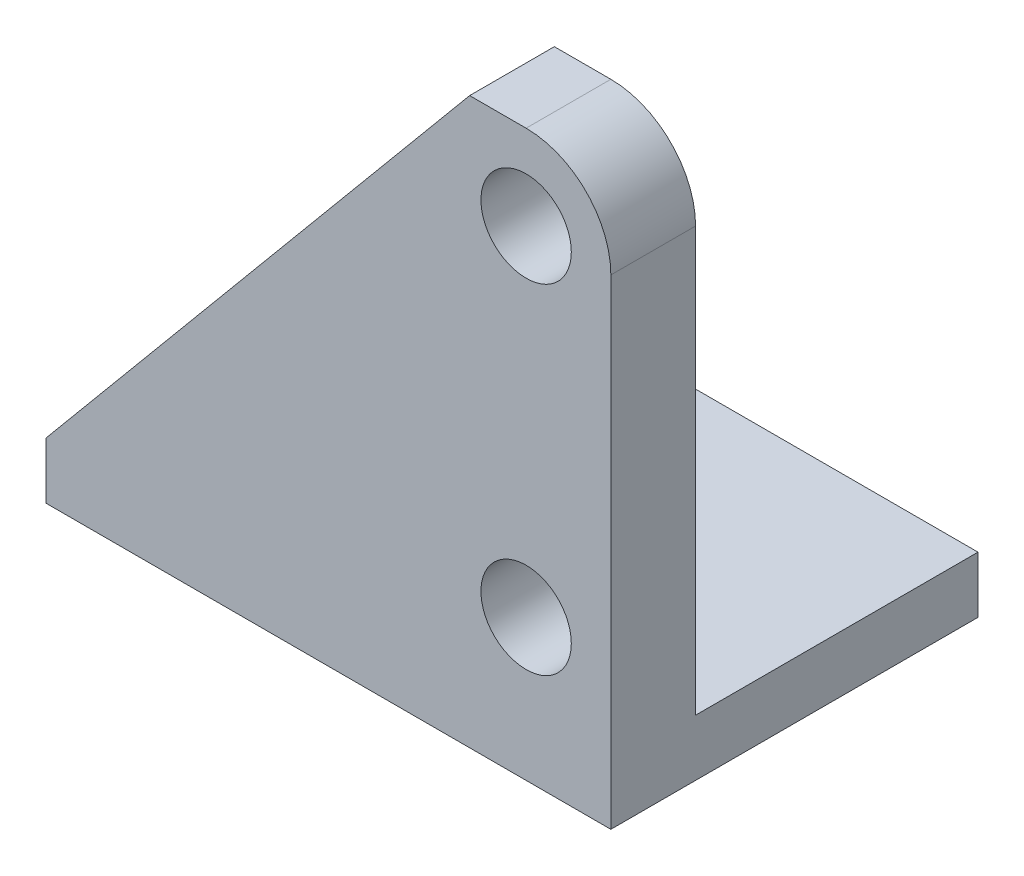
SolidWorks part; units mm, degrees
ref_plane "前视基准面" through (0, 0, 0) normal (0, 0, 1) x (1, 0, 0)
ref_plane "上视基准面" through (0, 0, 0) normal (0, 1, 0) x (1, 0, 0)
ref_plane "右视基准面" through (0, 0, 0) normal (1, 0, 0) x (0, 0, -1)
sketch "草图1" plane through (0, 0, 0) normal (0, 0, 1) x (1, 0, 0)
  line L1 (0, 0) -> (20, 0)
  line L2 (0, 0) -> (0, 20)
  line L3 (0, 20) -> (17, 20)
  line L4 (20, 0) -> (20, 17)
  circle A0 centre (17, 17) radius 1.6
  circle A2 centre (17, 5) radius 1.6
  arc A3 (20, 17) -> (17, 20) centre (17, 17) ccw
  dimension "D1" = 2
  dimension "D2" = 3
extrude "凸台-拉伸1" add sketch "草图1" along normal blind 3
sketch "草图2" plane through (0, 0, 3) normal (0, 0, 1) x (1, 0, 0)
  line L0 (0, 20) -> (0, 0) construction
  line L1 (20, 0) -> (0, 0)
  line L2 (20, 0) -> (20, 2)
  line L3 (20, 2) -> (0, 2)
  line L4 (0, 0) -> (0, 2)
extrude "凸台-拉伸2" add sketch "草图2" against normal blind 13
sketch "草图3" plane through (0, 0, 3) normal (0, 0, 1) x (1, 0, 0)
  line L0 (0, 2) -> (15, 20)
  line L1 (17, 20) -> (0, 20) construction
  line L2 (15, 20) -> (0, 20)
  line L3 (0, 20) -> (0, 2)
extrude "切除-拉伸1" cut sketch "草图3" against normal blind 20
